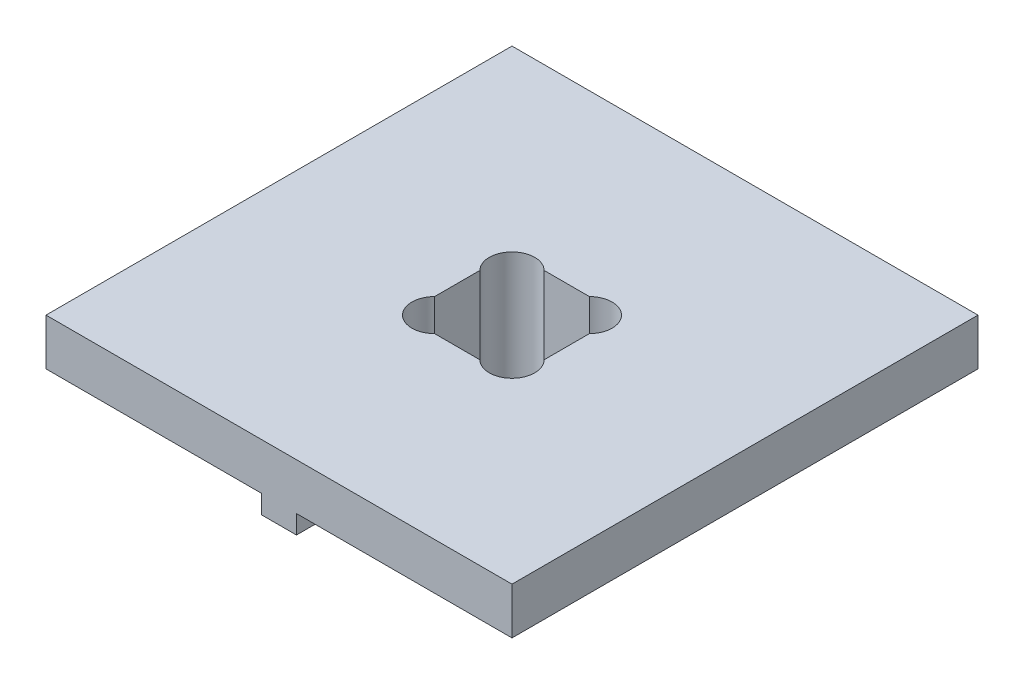
SolidWorks part; units mm, degrees
ref_plane "Front Plane" through (0, 0, 0) normal (0, 0, 1) x (1, 0, 0)
ref_plane "Top Plane" through (0, 0, 0) normal (0, 1, 0) x (1, 0, 0)
ref_plane "Right Plane" through (0, 0, 0) normal (1, 0, 0) x (0, 0, -1)
sketch "Sketch1" plane through (0, 0, 0) normal (0, 1, 0) x (1, 0, 0)
  line L1 (-2.9845, 2.9845) -> (2.9845, 2.9845)
  line L2 (-2.9845, 2.9845) -> (-2.9845, -2.9845)
  line L3 (-2.9845, -2.9845) -> (2.9845, -2.9845)
  line L4 (2.9845, 2.9845) -> (2.9845, -2.9845)
  line L5 (-12.7, 12.7) -> (12.7, 12.7)
  line L6 (-12.7, 12.7) -> (-12.7, -12.7)
  line L7 (-12.7, -12.7) -> (12.7, -12.7)
  line L8 (12.7, 12.7) -> (12.7, -12.7)
  point P8 (0, 12.7)
  point P9 (12.7, 0)
  point P11 (0, 2.9845)
  point P12 (-2.9845, 0)
  dimension "D1" = 5.969
  dimension "D2" = 25.4
extrude "Boss-Extrude1" add sketch "Sketch1" along normal blind 10.16
sketch "Sketch2" plane through (0, 0, 0) normal (0, -1, 0) x (1, 0, 0)
  line L0 (-2.9845, 2.9845) -> (2.9845, 2.9845) construction
  line L1 (0.9525, 2.9845) -> (-0.9525, 2.9845)
  line L2 (0.9525, 2.9845) -> (0.9525, 12.7)
  line L3 (0.9525, 12.7) -> (-0.9525, 12.7)
  line L4 (-0.9525, 2.9845) -> (-0.9525, 12.7)
  line L5 (-12.7, 12.7) -> (12.7, 12.7) construction
  point P8 (0, 2.9845)
  dimension "D1" = 1.905
extrude "Boss-Extrude2" add sketch "Sketch2" along normal blind 1.016
mirror "Mirror1" about plane through (0, 0, 0) normal (0, 0, 1) of "Boss-Extrude2"
sketch "Sketch3" plane through (0, 0, 0) normal (0, -1, 0) x (1, 0, 0)
  line L1 (-2.9845, 2.9845) -> (2.9845, 2.9845)
  line L2 (-2.9845, 2.9845) -> (-2.9845, -2.9845)
  line L3 (-2.9845, -2.9845) -> (2.9845, -2.9845)
  line L4 (2.9845, 2.9845) -> (2.9845, -2.9845)
  line L5 (-4.7244, 4.7244) -> (4.7244, 4.7244)
  line L6 (-4.7244, 4.7244) -> (-4.7244, -4.7244)
  line L7 (-4.7244, -4.7244) -> (4.7244, -4.7244)
  line L8 (4.7244, 4.7244) -> (4.7244, -4.7244)
  point P10 (0, 4.7244)
  point P11 (-4.7244, 0)
  dimension "D1" = 9.4488
extrude "Boss-Extrude3" add sketch "Sketch3" along normal blind 6
sketch "Sketch4" plane through (0, 0, 0) normal (0, -1, 0) x (1, 0, 0)
  line L0 (-0.9525, 12.7) -> (-0.9525, 4.7244) construction
  line L1 (0.9525, 4.7244) -> (-0.9525, 4.7244)
  line L2 (0.9525, 4.7244) -> (0.9525, 8.89)
  line L3 (0.9525, 8.89) -> (-0.9525, 8.89)
  line L4 (-0.9525, 4.7244) -> (-0.9525, 8.89)
  line L5 (-0.9525, -12.7) -> (-0.9525, -4.7244) construction
  line L6 (0.9525, -4.7244) -> (-0.9525, -4.7244)
  line L7 (0.9525, -4.7244) -> (0.9525, -8.89)
  line L8 (0.9525, -8.89) -> (-0.9525, -8.89)
  line L9 (-0.9525, -4.7244) -> (-0.9525, -8.89)
  line L10 (0.9525, 12.7) -> (-0.9525, 12.7) construction
  dimension "D1" = 3.81
extrude "Cut-Extrude2" cut sketch "Sketch4" along normal up to next
sketch "Sketch7" plane through (0, -6, 0) normal (0, -1, 0) x (1, 0, 0)
  line L1 (-2.9845, 2.9845) -> (-2.9845, 1.2345) construction
  line L2 (-2.9845, 2.9845) -> (-2.9845, -2.9845) construction
  line L3 (-2.9845, 2.9845) -> (-1.2345, 2.9845) construction
  line L4 (2.9845, 2.9845) -> (-2.9845, 2.9845) construction
  circle A0 centre (-2.1095, 2.1095) radius 1.2374
  circle A1 centre (-1.2345, 1.2345) radius 1.75 construction
  dimension "D1" = 3.5
extrude "Cut-Extrude5" cut sketch "Sketch7" against normal through all
mirror "Mirror3" about plane through (0, 0, 0) normal (1, 0, 0) of "Cut-Extrude5"
mirror "Mirror4" about plane through (0, 0, 0) normal (0, 0, 1) of "Mirror3", "Cut-Extrude5"
sketch "Sketch6" plane through (0, 10.16, 0) normal (0, 1, 0) x (1, 0, 0)
  line L4 (-12.7, 12.7) -> (-12.7, -12.7)
  line L5 (-12.7, -12.7) -> (12.7, -12.7)
  line L6 (12.7, -12.7) -> (12.7, 12.7)
  line L7 (12.7, 12.7) -> (-12.7, 12.7)
  line L8 (-12.7, 12.7) -> (-12.7, -12.7)
  line L9 (-12.7, -12.7) -> (12.7, -12.7)
  line L10 (12.7, -12.7) -> (12.7, 12.7)
  line L11 (12.7, 12.7) -> (-12.7, 12.7)
  dimension "D1" = 0
extrude "Cut-Extrude4" cut sketch "Sketch6" against normal offset from surface (7.62 mm away) 2.54 up to face at (0, 0, 0)
fillet "Fillet1" radius 1.778 4 edges at (-4.7244, -3, 4.7244) (4.7244, -3, 4.7244) (-4.7244, -3, -4.7244) (4.7244, -3, -4.7244)
